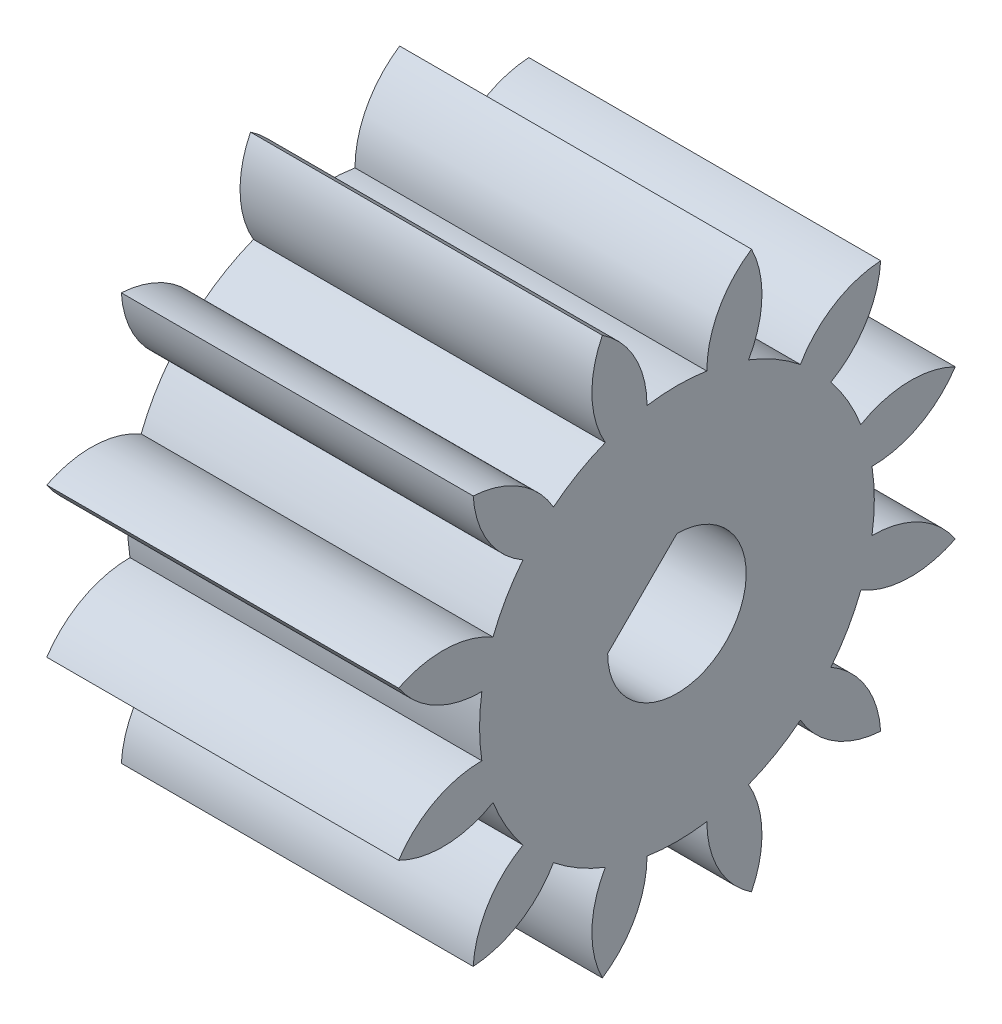
SolidWorks part; units mm, degrees
ref_plane "Plane1" through (0, 0, 0) normal (0, 0, 1) x (1, 0, 0)
ref_plane "Plane2" through (0, 0, 0) normal (0, 1, 0) x (1, 0, 0)
ref_plane "Plane3" through (0, 0, 0) normal (1, 0, 0) x (0, 0, -1)
other "Configuration Table"
sketch "HoldingSke" plane through (0, 0, 0) normal (0, 1, 0) x (1, 0, 0)
  line L0 (0, 0) -> (0.6496, -0.15)
  line L1 (-15, 0) -> (100, 0) construction
  line L2 (0, 0) -> (-2.1039, 2.3779)
  line L3 (0, 0) -> (-11.863, 4.5341)
  line L4 (0, 0) -> (8.4473, 1.7955)
  line L5 (0, 0) -> (-23.7986, -8.8762)
  line L6 (0, 0) -> (-10.5278, -7.1032)
  line L7 (-2.1039, 2.3779) -> (3.3635, 27.1825)
  line L8 (-76.2, 54.61) -> (-73.66, 54.61)
  line L9 (-71.009, 38.7566) -> (-53.1078, 45.2721)
  line L10 (-76.2, 71.12) -> (104.1128, 71.12)
  line L11 (0, 0) -> (-12.7, 0)
  line L12 (-76.2, 101.6) -> (-75.9714, 101.6)
  line L13 (24.9733, 27.94) -> (52.9518, 28.4284)
  line L14 (24.9733, 27.94) -> (24.9746, 27.94)
  line L15 (24.9733, 27.94) -> (100.4006, 29.5858)
  line L16 (-63.627, -1.5) -> (-12.827, -1.5)
  circle A0 centre (0, 0) radius 2.5
  circle A1 centre (0, 0) radius 7.1237
  circle A2 centre (0, 0) radius 12.7
  circle A3 centre (0, 0) radius 2.5
  dimension "MHD" = 14.2475
  dimension "Hub_dia" = 25.4
  dimension "Bore" = 5
  dimension "MBD" = 5
  dimension "Num_teeth" = 12
  dimension "Pitch" = 0.6667
  dimension "Overall_len" = 25.4
  dimension "Show_teeth" = 13
  dimension "Thickness" = 12.7
  dimension "OAL" = 25.4001
  dimension "T_dim" = 2.54
  dimension "Ap" = 20
  dimension "H" = 19.05
  dimension "Pitch_radius" = 180.3128
  dimension "Width" = 12.7
  dimension "Backlash" = 0.2286
  dimension "Addendum_fac" = 1
  dimension "Dedendum_fac" = 1.25
  dimension "Clearance_fac" = 0.25
  dimension "Dedendum_add" = 0.0013
  dimension "Module" = 1.5
sketch "BasProSke" plane through (0, 0, 0) normal (0, 1, 0) x (1, 0, 0)
  line L0 (-10, 0) -> (60, 0) construction
  line L1 (0, 0) -> (0, 10.5)
  line L2 (0, 0) -> (12.7, 0)
  line L3 (12.7, 0) -> (12.7, 10.5)
  line L4 (12.7, 10.5) -> (0, 10.5)
  dimension "Thickness" = 12.7
  dimension "Diameter" = 21
revolve "Base-Revolve" add sketch "BasProSke" angle 360 about L0
sketch "TooCutSke" plane through (0, 0, 0) normal (1, 0, 0) x (0, 0, -1)
  line L1 (0, 0) -> (0, 107) construction
  line L2 (0, 0) -> (-1.5724, 8.8616) construction
  line L3 (0, 0) -> (-4.6415, 17.3221) construction
  line L4 (-1.5724, 8.8616) -> (-2.3207, 8.6611) construction
  arc A0 (1.0801, 7.0414) -> (-1.0801, 7.0414) centre (0, 0) ccw
  arc A1 (2.836, 10.1361) -> (-2.836, 10.1361) centre (0, 0) ccw
  circle A2 centre (0, 0) radius 9 construction
  circle A3 centre (0, 0) radius 8.4572 construction
  arc A4 (-1.0801, 7.0414) -> (-2.836, 10.1361) centre (-4.6801, 7.0443) ccw
  arc A5 (2.836, 10.1361) -> (1.0801, 7.0414) centre (4.6801, 7.0443) ccw
  dimension "Root_dia" = 14.2475
  dimension "Overcut_dia" = 21.0508
  dimension "Pitch_dia" = 18
  dimension "Base_dia" = 16.9145
  dimension "Flank_rad" = 3.6
  dimension "Half_ang" = 15
  dimension "Half_CT" = 0.7747
extrude "ToothCut" cut sketch "TooCutSke" along normal through all
fillet "Breaks" [suppressed] radius 0.03
fillet "RootFillets" [suppressed] radius 0.3763
pattern_circular "TeethCuts" count 12 every 30 about axis through (-10, 0, 0) along (1, 0, 0) of "ToothCut", "RootFillets", "Breaks"
sketch "HubNeaOneSke" plane through (0, 0, 0) normal (-1, 0, 0) x (0, 0, 1)
  circle A0 centre (0, 0) radius 7.1237
  dimension "Diameter" = 14.2475
extrude "HubNearOne" [suppressed] add sketch "HubNeaOneSke" along normal blind 12.7001
sketch "HubNeaBotSke" plane through (0, 0, 0) normal (-1, 0, 0) x (0, 0, 1)
  circle A0 centre (0, 0) radius 7.1237
  dimension "Diameter" = 14.2475
extrude "HubNearBoth" [suppressed] add sketch "HubNeaBotSke" along normal blind 6.35
ref_plane "FarPln" through (12.7, 0, 0) normal (1, 0, 0) x (0, 0, -1)
sketch "HubFarSke" plane through (12.7, 0, 0) normal (1, 0, 0) x (0, 0, -1)
  circle A0 centre (0, 0) radius 7.1237
  dimension "Diameter" = 14.2475
extrude "HubFar" [suppressed] add sketch "HubFarSke" along normal blind 6.35
sketch "BorSke" plane through (0, 0, 0) normal (1, 0, 0) x (0, 0, -1)
  circle A0 centre (0, 0) radius 2.5
  dimension "Diameter" = 5
extrude "Bore" cut sketch "BorSke" along normal mid plane 50.8001
sketch "KeySke" plane through (0, 0, 0) normal (1, 0, 0) x (0, 0, -1)
  line L0 (-3.175, 0) -> (-3.175, 5.04)
  line L1 (-3.175, 5.04) -> (3.175, 5.04)
  line L2 (3.175, 5.04) -> (3.175, 0)
  line L3 (0, 0) -> (0, 34) construction
  line L4 (-3.175, 0) -> (3.175, 0)
  dimension "Offset" = 5.04
  dimension "Width" = 6.35
extrude "Keyway" [suppressed] cut sketch "KeySke" along normal mid plane 50.8001
pattern_circular "Keyway2" [suppressed] count 2 every 90 about axis through (-10, 0, 0) along (1, 0, 0)
sketch "Sketch1" [suppressed] plane through (10, 0, 0) normal (1, 0, 0) x (0, 0, -1)
  line L0 (0, -2.5) -> (2.5, 0)
  line L1 (2.5, 0) -> (0, 0) construction
  line L2 (0, 0) -> (0, -2.5) construction
  arc A0 (0, -2.5) -> (2.5, 0) centre (0, 0) ccw
  circle A1 centre (0, 0) radius 2.5 construction
extrude "Boss-Extrude1" [suppressed] add sketch "Sketch1" against normal through all
sketch "Sketch2" plane through (12.7, 0, 0) normal (1, 0, 0) x (0, 0, -1)
  line L0 (0, 0) -> (-2.5, 0) construction
  line L1 (-2.5, 0) -> (0, 2.5)
  line L2 (0, 0) -> (0, 2.5) construction
  arc A0 (-2.5, 0) -> (0, 2.5) centre (0, 0) cw
  circle A1 centre (0, 0) radius 2.5 construction
extrude "Boss-Extrude2" add sketch "Sketch2" against normal through all
equation "' \"Module@HoldingSke\" = 6.35"
equation "' \"Num_teeth@HoldingSke\" = 12"
equation "' \"Ap@HoldingSke\" =  20"
equation "' \"Ap@HoldingSke\" = 20"
equation "' \"Width@HoldingSke\" = 0.5 * 25.4"
equation "' \"Hub_dia@HoldingSke\"= 1 * 25.4"
equation "' \"Hub_dia@HoldingSke\" = 1 * 25.4"
equation "' \"Overall_len@HoldingSke\" = 1.0 * 25.4"
equation "' \"Bore@HoldingSke\" = 0.75 * 25.4"
equation "' \"T_dim@HoldingSke\" = 0.1 * 25.4"
equation "' \"Width@KeySke\" = 0.25 * 25.4"
equation "' \"Show_teeth@HoldingSke\" = 13"
equation "' \"Backlash@HoldingSke\" = 0.009 * 25.4"
equation "' \"Addendum_fac@HoldingSke\" = 1.0"
equation "' \"Dedendum_fac@HoldingSke\" = 1.25"
equation "' \"Dedendum_add@HoldingSke\" = 0.00005 * 25.4"
equation "' \"Clearance_fac@HoldingSke\" = 0.25"
equation "\"Pitch@HoldingSke\" = 1 / \"Module@HoldingSke\""
equation "\"Overcut_dia@TooCutSke\" = (\"Num_teeth@HoldingSke\" + 2 * \"Addendum_fac@HoldingSke\") / \"Pitch@HoldingSke\" + 0.002 * 25.4"
equation "\"Pitch_dia@TooCutSke\" = \"Num_teeth@HoldingSke\" / \"Pitch@HoldingSke\""
equation "\"Base_dia@TooCutSke\" = \"Num_teeth@HoldingSke\" / \"Pitch@HoldingSke\" * cos((\"Ap@HoldingSke\"  * 3.14159265 / 180))"
equation "\"Root_dia@TooCutSke\" = (\"Num_teeth@HoldingSke\" + 2) / \"Pitch@HoldingSke\" - 2 * (\"Addendum_fac@HoldingSke\" + \"Dedendum_fac@HoldingSke\") / \"Pitch@HoldingSke\" - \"Dedendum_add@HoldingSke\" * 2"
equation "\"Half_ang@TooCutSke\" = 180 / \"Num_teeth@HoldingSke\""
equation "\"Half_CT@TooCutSke\" = \"Num_teeth@HoldingSke\" / \"Pitch@HoldingSke\" * sin((3.14159265 / 2 / \"Num_teeth@HoldingSke\")) / 2 - 7 * \"Backlash@HoldingSke\" / 4"
equation "\"Flank_rad@TooCutSke\" = \"Num_teeth@HoldingSke\" / \"Pitch@HoldingSke\" / 5"
equation "\"Radius@RootFillets\" = \"Clearance_fac@HoldingSke\" / \"Pitch@HoldingSke\" + \"Dedendum_add@HoldingSke\""
equation "\"Break_rad@Breaks\" = 0.02 / \"Pitch@HoldingSke\""
equation "\"Thickness@HoldingSke\" = \"Width@HoldingSke\""
equation "\"OAL@HoldingSke\" = \"Thickness@HoldingSke\""
equation "\"MHD@HoldingSke\" = (\"Num_teeth@HoldingSke\" + 2) / \"Pitch@HoldingSke\" - 2 * (\"Addendum_fac@HoldingSke\" + \"Dedendum_fac@HoldingSke\")  / \"Pitch@HoldingSke\" - \"Dedendum_add@HoldingSke\" * 2"
equation "\"MBD@HoldingSke\" = (\"Num_teeth@HoldingSke\" + 2) / \"Pitch@HoldingSke\" - 2 * (\"Addendum_fac@HoldingSke\" + \"Dedendum_fac@HoldingSke\")  / \"Pitch@HoldingSke\" - \"Dedendum_add@HoldingSke\" * 2 - 0.002 * 25.4"
equation "\"MHD@HoldingSke\" = ((sgn( \"MHD@HoldingSke\" - \"Hub_dia@HoldingSke\" )-1)*( \"MHD@HoldingSke\" - \"Hub_dia@HoldingSke\" ))/-2+ \"Hub_dia@HoldingSke\""
equation "\"MBD@HoldingSke\" = ((sgn( \"MBD@HoldingSke\" - \"Bore@HoldingSke\" )-1)*( \"MBD@HoldingSke\" - \"Bore@HoldingSke\" ))/-2+ \"Bore@HoldingSke\""
equation "\"OAL@HoldingSke\" = ((sgn( \"OAL@HoldingSke\" - \"Overall_len@HoldingSke\" )+1)*( \"OAL@HoldingSke\" - \"Overall_len@HoldingSke\" ))/2 + \"Overall_len@HoldingSke\" + 0.000002 * 25.4"
equation "\"Num_teeth@TeethCuts\" = int( \"Show_teeth@HoldingSke\" ) + 1"
equation "\"Num_teeth@TeethCuts\" = ((sgn( \"Num_teeth@TeethCuts\" - \"Num_teeth@HoldingSke\" )-1)*( \"Num_teeth@TeethCuts\" - \"Num_teeth@HoldingSke\" ))/-2+ \"Num_teeth@HoldingSke\""
equation "\"Num_teeth@TeethCuts\" = ((sgn( \"Num_teeth@TeethCuts\" - 2.0)+1)*( \"Num_teeth@TeethCuts\" - 2.0))/2 +2.0"
equation "\"Angle@TeethCuts\" = 360.0 / \"Num_teeth@HoldingSke\""
equation "\"Diameter@BasProSke\" = (\"Num_teeth@HoldingSke\" + 2 * \"Addendum_fac@HoldingSke\") / \"Pitch@HoldingSke\""
equation "\"Thickness@BasProSke\"  = \"Thickness@HoldingSke\""
equation "' \"Fillet_rad@BasProSke\" =  \"Thickness@HoldingSke\" * 0.05"
equation "' \"Fillet_rad@BasProSke\" = \"Thickness@HoldingSke\" * 0.05"
equation "\"MHD@HoldingSke\" = ((sgn( \"MHD@HoldingSke\" - \"Root_dia@TooCutSke\" )-1)*( \"MHD@HoldingSke\" - \"Root_dia@TooCutSke\" ))/-2+ \"Root_dia@TooCutSke\""
equation "\"Diameter@HubNeaOneSke\" = \"MHD@HoldingSke\""
equation "\"Length@HubNearOne\" = \"OAL@HoldingSke\" - \"Thickness@BasProSke\""
equation "\"Diameter@HubNeaBotSke\" = \"MHD@HoldingSke\""
equation "\"Length@HubNearBoth\" = ( \"OAL@HoldingSke\" - \"Thickness@BasProSke\" ) / 2.0"
equation "\"Thickness@FarPln\" = \"Thickness@BasProSke\""
equation "\"Diameter@HubFarSke\" = \"MHD@HoldingSke\""
equation "\"Length@HubFar\" = ( \"OAL@HoldingSke\" - \"Thickness@BasProSke\" ) / 2.0"
equation "\"Diameter@BorSke\" = \"MBD@HoldingSke\""
equation "\"D1@Bore\" = \"OAL@HoldingSke\" * 2.0"
equation "\"D1@Keyway\" = \"OAL@HoldingSke\" * 2.0"
equation "\"Offset@KeySke\" = \"T_dim@HoldingSke\" + \"MBD@HoldingSke\" / 2.0"
